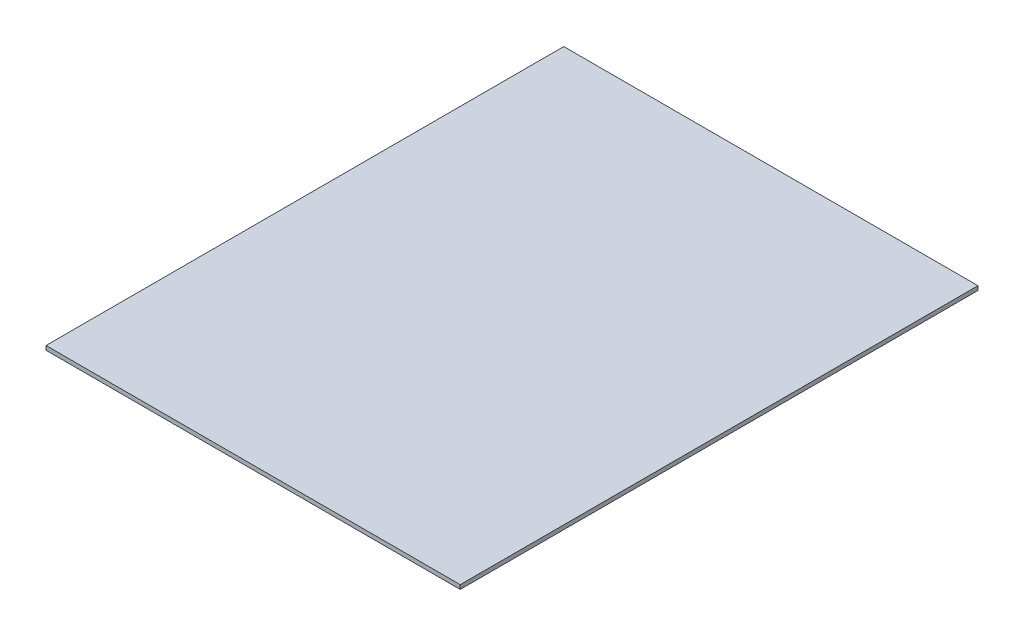
SolidWorks part; units mm, degrees
ref_plane "Front Plane" through (0, 0, 0) normal (0, 0, 1) x (1, 0, 0)
ref_plane "Top Plane" through (0, 0, 0) normal (0, 1, 0) x (1, 0, 0)
ref_plane "Right Plane" through (0, 0, 0) normal (1, 0, 0) x (0, 0, -1)
sketch "Sketch1" plane through (0, 0, 0) normal (0, 1, 0) x (1, 0, 0)
  line L1 (-2000, -2500) -> (2000, -2500)
  line L2 (-2000, -2500) -> (-2000, 2500)
  line L3 (-2000, 2500) -> (2000, 2500)
  line L4 (2000, -2500) -> (2000, 2500)
  line L5 (-2000, -2500) -> (2000, 2500) construction
  line L6 (-2000, 2500) -> (2000, -2500) construction
  point P0 (0, 0)
  dimension "D1" = 4000
  dimension "D2" = 5000
extrude "Boss-Extrude1" add sketch "Sketch1" along normal blind 40
